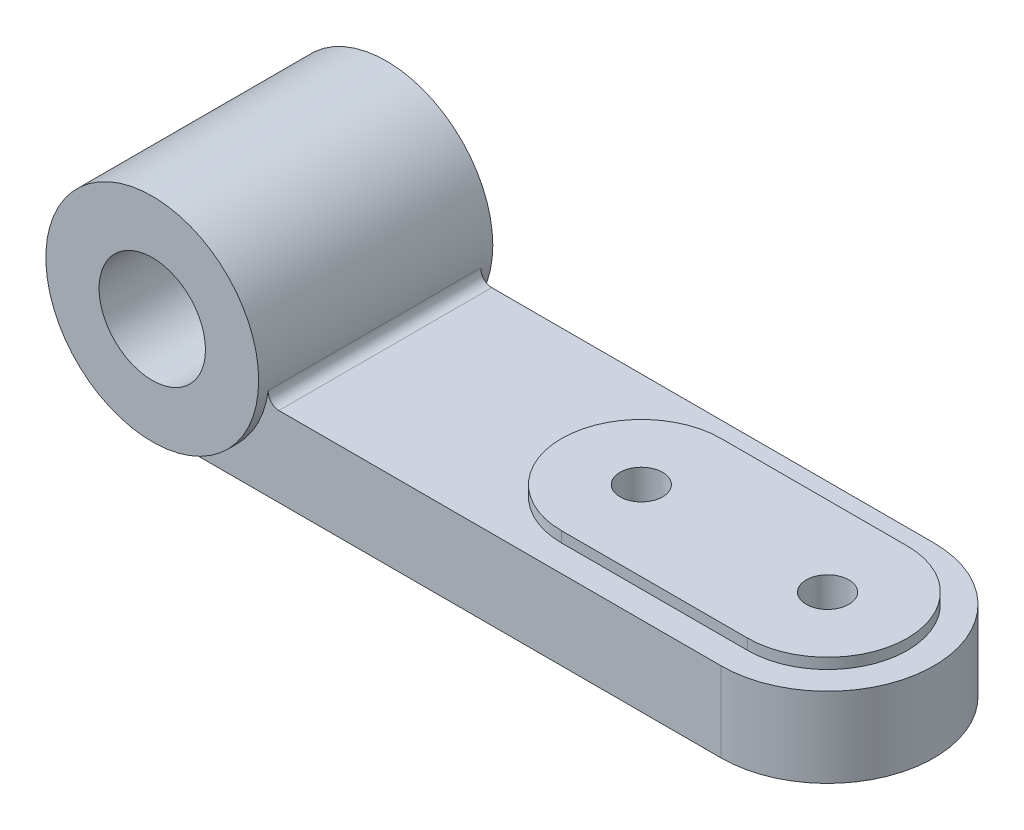
SolidWorks part; units mm, degrees
ref_plane "Front Plane" through (0, 0, 0) normal (0, 0, 1) x (1, 0, 0)
ref_plane "Top Plane" through (0, 0, 0) normal (0, 1, 0) x (1, 0, 0)
ref_plane "Right Plane" through (0, 0, 0) normal (1, 0, 0) x (0, 0, -1)
sketch "Sketch1" plane through (0, 0, 0) normal (0, 1, 0) x (1, 0, 0)
  line L1 (-52.5, 20) -> (52.5, 20)
  line L2 (-52.5, 20) -> (-52.5, -20)
  line L3 (-52.5, -20) -> (52.5, -20)
  line L4 (52.5, 20) -> (52.5, 15) construction
  line L5 (52.5, 4) -> (52.5, -5.6612)
  line L6 (52.5, 15) -> (52.5, 4) construction
  line L8 (52.5, -15) -> (52.5, -20) construction
  circle A0 centre (17.5, 0) radius 4
  circle A1 centre (52.5, 0) radius 4
  arc A3 (52.5, 20) -> (52.5, -20) centre (52.5, 0) cw
  point P0 (0, 0)
extrude "Boss-Extrude1" add sketch "Sketch1" along normal blind 15
sketch "Sketch3" plane through (0, 0, 0) normal (0, 0, 1) x (1, 0, 0)
  circle A0 centre (-52.4116, 19.9998) radius 20
  dimension "D1" = 20
extrude "Boss-Extrude2" add sketch "Sketch3" along normal blind 22 and the other way blind 22
sketch "Sketch4" plane through (0, 0, 22) normal (0, 0, 1) x (1, 0, 0)
  circle A0 centre (-52.4116, 19.9998) radius 10
extrude "Cut-Extrude1" cut sketch "Sketch4" against normal through all
sketch "Sketch5" plane through (0, 15, 0) normal (0, 1, 0) x (1, 0, 0)
  line L0 (17.5, 15) -> (52.5, 15)
  line L1 (17.5, -15) -> (52.5, -15)
  arc A0 (52.5, -15) -> (52.5, 15) centre (52.5, 0) ccw
  arc A1 (17.5, 15) -> (17.5, -15) centre (17.5, 0) ccw
  circle A2 centre (17.5, 0) radius 4
  circle A3 centre (52.5, 0) radius 4
extrude "Boss-Extrude3" add sketch "Sketch5" along normal blind 2
fillet "Fillet2" radius 2 1 edges at (-33.0466, 15, 0)
